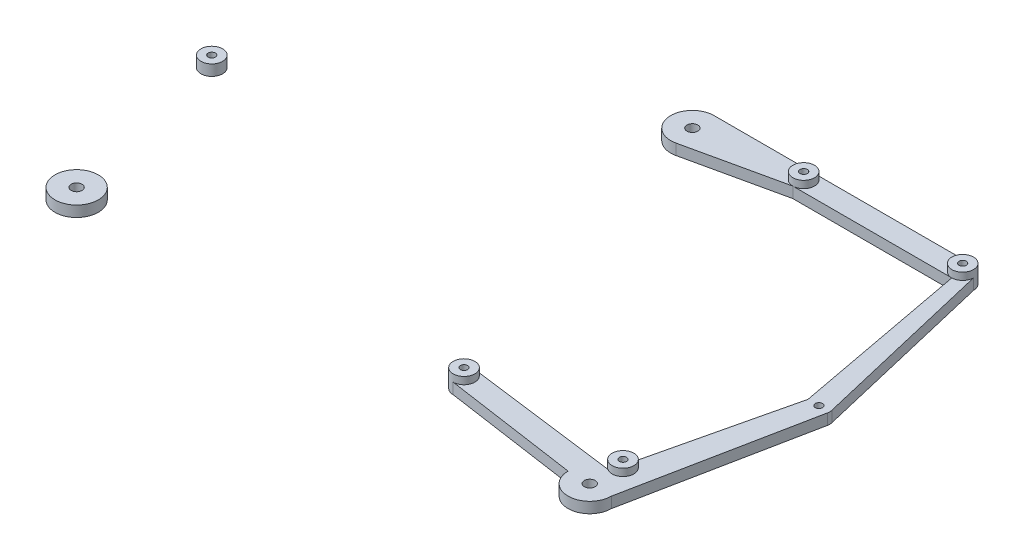
SolidWorks part; units mm, degrees
ref_plane "Front Plane" through (0, 0, 0) normal (0, 0, 1) x (1, 0, 0)
ref_plane "Top Plane" through (0, 0, 0) normal (0, 1, 0) x (1, 0, 0)
ref_plane "Right Plane" through (0, 0, 0) normal (1, 0, 0) x (0, 0, -1)
sketch "Sketch1" plane through (0, 53.5, 0) normal (0, 1, 0) x (1, 0, 0)
  circle A0 centre (-36, -88.75) radius 1.5 construction
  circle A1 centre (-36, -88.75) radius 6 construction
  circle A2 centre (35, 10.65) radius 1.5 construction
  circle A3 centre (35, 10.65) radius 6 construction
  circle A4 centre (106, -88.75) radius 1.5 construction
  circle A5 centre (106, -88.75) radius 6 construction
  circle A6 centre (-36, -88.75) radius 1.5
  circle A7 centre (-36, -88.75) radius 6
  circle A8 centre (35, 10.65) radius 1.5
  circle A9 centre (35, 10.65) radius 6
  circle A10 centre (106, -88.75) radius 1.5
  circle A11 centre (106, -88.75) radius 6
  circle A12 centre (119, -38.35) radius 1 construction
  circle A13 centre (-49, -38.35) radius 1 construction
  circle A14 centre (119, -38.35) radius 1
  circle A15 centre (-49, -38.35) radius 1
  circle A16 centre (119, -38.35) radius 3
  circle A17 centre (-49, -38.35) radius 3
  dimension "D1" = 2
  dimension "D2" = 2
extrude "AudioHolder links" add sketch "Sketch1" along normal blind 3
sketch "Limit profile" plane through (0, 53.5, 0) normal (0, -1, 0) x (1, 0, 0)
  line L4 (-47, -19.15) -> (117, -19.15)
  line L5 (117, -19.15) -> (117, 95.85)
  line L6 (117, 95.85) -> (-47, 95.85)
  line L7 (-47, 95.85) -> (-47, -19.15)
  line L8 (-47, -19.15) -> (117, -19.15)
  line L9 (117, -19.15) -> (117, 95.85)
  line L10 (117, 95.85) -> (-47, 95.85)
  line L11 (-47, 95.85) -> (-47, -19.15)
  dimension "D1" = 0
sketch "Sketch3" plane through (0, 56.5, 0) normal (0, 1, 0) x (1, 0, 0)
  line L0 (117, 19.15) -> (117, -95.85) construction
  line L1 (38.8, 17.05) -> (117, 17.05) construction
  line L2 (38.8, 17.05) -> (38.8, -83.75) construction
  line L3 (38.8, -83.75) -> (117, -83.75) construction
  line L4 (117, 17.05) -> (117, -83.75) construction
  line L5 (62.8, 13.65) -> (106.8, 13.65) construction
  line L6 (62.8, 13.65) -> (62.8, -80.35) construction
  line L7 (62.8, -80.35) -> (106.8, -80.35) construction
  line L8 (106.8, 13.65) -> (106.8, -80.35) construction
  line L10 (35, 16.65) -> (62.8, 16.65) construction
  circle A0 centre (106.8, 13.65) radius 1
  circle A1 centre (62.8, 13.65) radius 1
  circle A2 centre (62.8, -80.35) radius 1
  circle A3 centre (106.8, -80.35) radius 1
  circle A4 centre (106.8, 13.65) radius 3
  circle A5 centre (62.8, 13.65) radius 3
  circle A6 centre (62.8, -80.35) radius 3
  circle A7 centre (106.8, -80.35) radius 3
  circle A8 centre (35, 10.65) radius 6 construction
  circle A9 centre (35, 10.65) radius 6 construction
  point P4 (62.8, -33.35)
  point P9 (38.8, -33.35)
  point P24 (0, 0)
  point P25 (35, 16.65)
  point P26 (31.6411, 16.0217)
  point P28 (35, 16.65)
  dimension "D7" = 2
  dimension "D8" = 2
  dimension "D1" = 78.2
  dimension "D2" = 100.8
  dimension "D3" = 44
  dimension "D4" = 94
  dimension "D5" = 10.2
extrude "Modem standoffs" add sketch "Sketch3" along normal blind 2 and the other way up to surface other way up to face at (106, 53.5, 94.75)
sketch "Sketch4" plane through (0, 53.5, 0) normal (0, -1, 0) x (1, 0, 0)
  line L0 (109.8, -13.65) -> (121.9197, 37.6604)
  line L1 (112, 88.75) -> (121.942, 38.9372)
  line L2 (106.8, 77.35) -> (116, 38.35)
  line L3 (116, 38.35) -> (106.8, -10.65)
  line L4 (106.8, -16.65) -> (62.8, -16.65)
  line L5 (62.8, -16.65) -> (35, -16.65)
  line L6 (100, 88.75) -> (62.8, 83.35)
  line L7 (63.1864, 77.375) -> (105.0953, 82.8186)
  line L8 (36.295, -4.7914) -> (62.8, -10.65)
  line L9 (62.8, -10.65) -> (106.8, -10.65)
  circle A0 centre (119, 38.35) radius 1 construction
  circle A1 centre (119, 38.35) radius 3 construction
  circle A2 centre (106.8, -13.65) radius 1 construction
  circle A3 centre (106.8, -13.65) radius 3 construction
  circle A4 centre (62.8, -13.65) radius 1 construction
  circle A5 centre (62.8, -13.65) radius 3 construction
  circle A6 centre (35, -10.65) radius 1.5 construction
  circle A7 centre (35, -10.65) radius 6 construction
  circle A8 centre (119, 38.35) radius 1
  arc A9 (121.9197, 37.6604) -> (121.942, 38.9372) centre (119, 38.35) ccw
  circle A10 centre (106.8, -13.65) radius 1
  arc A11 (106.8, -16.65) -> (109.8, -13.65) centre (106.8, -13.65) ccw
  circle A12 centre (62.8, -13.65) radius 1
  circle A14 centre (35, -10.65) radius 1.5
  arc A15 (36.295, -4.7914) -> (35, -16.65) centre (35, -10.65) ccw
  circle A16 centre (106, 88.75) radius 1.5 construction
  arc A17 (108.0081, 83.096) -> (105.0953, 82.8186) centre (106, 88.75) ccw construction
  circle A18 centre (106.8, 80.35) radius 3 construction
  circle A19 centre (106.8, 80.35) radius 1 construction
  circle A20 centre (62.8, 80.35) radius 1 construction
  circle A21 centre (62.8, 80.35) radius 3 construction
  circle A22 centre (106, 88.75) radius 1.5
  arc A23 (112, 88.75) -> (100, 88.75) centre (106, 88.75) ccw
  arc A24 (105.0953, 82.8186) -> (106.8, 77.35) centre (106.8, 80.35) ccw
  circle A25 centre (106.8, 80.35) radius 1
  circle A26 centre (62.8, 80.35) radius 1
  arc A27 (62.8, 83.35) -> (63.1864, 77.375) centre (62.8, 80.35) ccw
  point P19 (0, 0)
  point P21 (0, 0)
  point P23 (0, 0)
extrude "Screwhole links 1" add sketch "Sketch4" against normal up to surface (3 mm away) up to face at (105.9734, 56.5, 89.0297)
